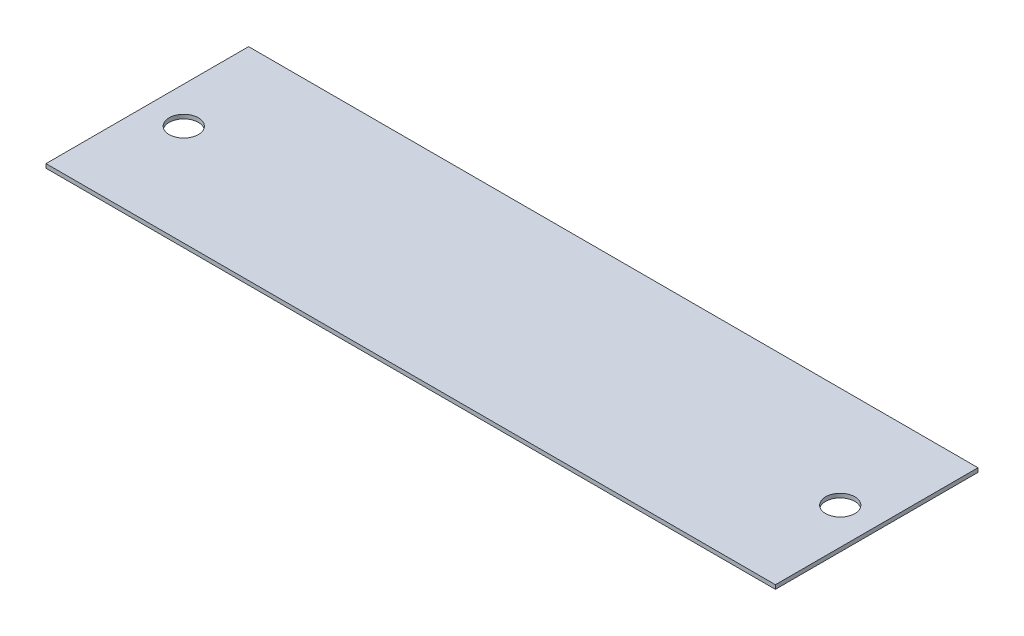
SolidWorks part; units mm, degrees
ref_plane "Alzado" through (0, 0, 0) normal (0, 0, 1) x (1, 0, 0)
ref_plane "Planta" through (0, 0, 0) normal (0, 1, 0) x (1, 0, 0)
ref_plane "Vista lateral" through (0, 0, 0) normal (1, 0, 0) x (0, 0, -1)
sketch "Croquis1" plane through (0, 0, 0) normal (0, 1, 0) x (1, 0, 0)
  line L1 (-45, 12.5) -> (45, 12.5)
  line L2 (-45, 12.5) -> (-45, -12.5)
  line L3 (-45, -12.5) -> (45, -12.5)
  line L4 (45, 12.5) -> (45, -12.5)
  line L5 (-45, 12.5) -> (45, -12.5) construction
  line L6 (-45, -12.5) -> (45, 12.5) construction
  point P0 (0, 0)
  dimension "D1" = 25
  dimension "D2" = 90
extrude "Saliente-Extruir1" add sketch "Croquis1" along normal blind 0.5
sketch "Croquis2" plane through (0, 0.5, 0) normal (0, 1, 0) x (1, 0, 0)
  line L0 (-45, 12.5) -> (-45, -12.5) construction
  circle A0 centre (-40.5, 0) radius 1.8
  circle A1 centre (40.5, 0) radius 1.8
  point P4 (0, 0)
  dimension "D3" = 3.6
  dimension "D1" = 81
  dimension "D2" = 4.5
extrude "Cortar-Extruir1" cut sketch "Croquis2" against normal up to surface (0.5 mm away) up to face at (0, 0, 0)
